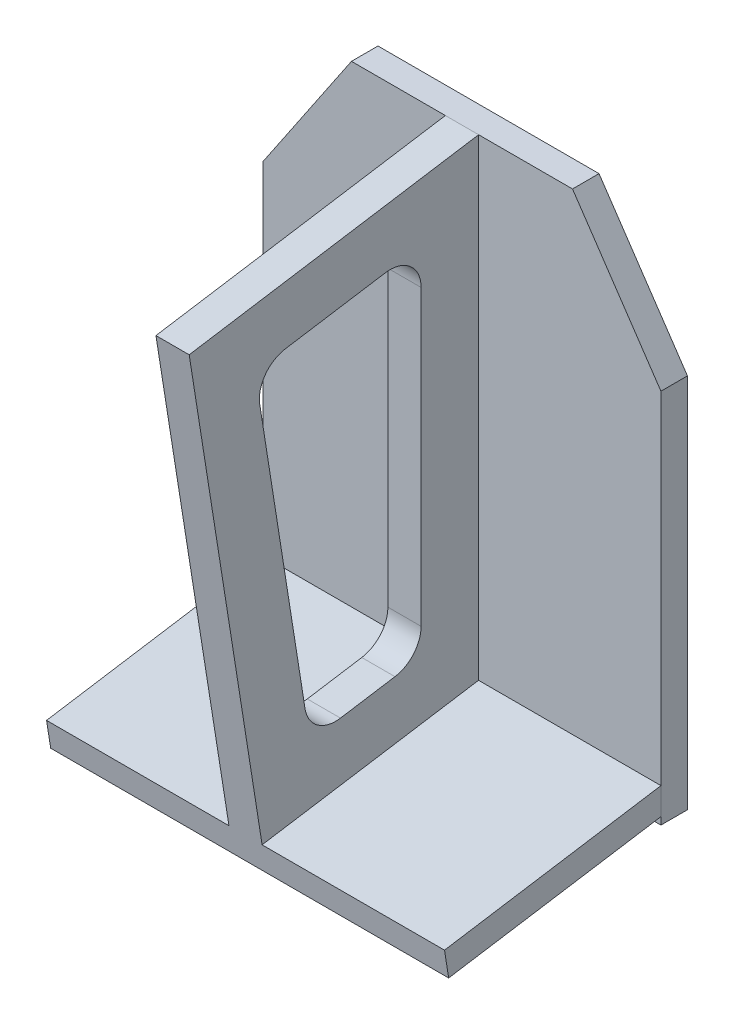
SolidWorks part; units mm, degrees
ref_plane "Front Plane" through (0, 0, 0) normal (0, 0, 1) x (1, 0, 0)
ref_plane "Top Plane" through (0, 0, 0) normal (0, 1, 0) x (1, 0, 0)
ref_plane "Right Plane" through (0, 0, 0) normal (1, 0, 0) x (0, 0, -1)
sketch "Sketch1" plane through (0, 0, 0) normal (0, 0, 1) x (1, 0, 0)
  line L0 (0, 0) -> (0, -68) construction
  line L11 (-45, -68) -> (45, -68)
  line L14 (45, -68) -> (45, 17)
  line L15 (45, 17) -> (25, 46.6204)
  line L16 (25, 46.6204) -> (-25, 46.6204)
  line L17 (-45, -68) -> (-45, 17)
  line L18 (-45, 17) -> (-25, 46.6204)
  point P9 (0, 46.6204)
  dimension "D1" = 90
  dimension "D2" = 85
  dimension "D3" = 50
  dimension "D4" = 68
extrude "Boss-Extrude1" add sketch "Sketch1" along normal blind 6
sketch "Sketch2" plane through (0, -10.1552, 64.1172) normal (0, 0.1564, -0.9877) x (-1, 0, 0)
  line L0 (190, -43.4228) -> (-190, -43.4228) construction
  line L1 (-190, -75.1728) -> (190, -75.1728) construction
  line L2 (190, -43.4228) -> (-190, -43.4228)
  line L3 (-190, -75.1728) -> (190, -75.1728)
  line L4 (-0.1819, -44.9338) -> (-0.0251, -58.5843) construction
  line L5 (-45, -67.1628) -> (-45, 16.7907) construction
  line L6 (45.0187, -64.5843) -> (-45, -64.5843)
  line L7 (45.0187, -64.5843) -> (45.0187, -58.5843)
  line L8 (45.0187, -58.5843) -> (3.7593, -58.5843)
  line L9 (-45, -64.5843) -> (-45, -58.5843)
  line L13 (-25, 46.9851) -> (25, 46.9851) construction
  line L14 (0.0091, -58.5843) -> (0, 46.9851) construction
  line L15 (-3.74, -64.5849) -> (-3.74, -64.5843)
  line L16 (-3.7593, 46.9844) -> (3.7593, 46.9851)
  line L17 (0.0091, -58.5843) -> (-0.0251, -58.5843)
  line L18 (0.0438, -64.5843) -> (0.2006, -78.2347) construction
  line L19 (-3.741, -58.5843) -> (-45, -58.5843)
  line L20 (-3.741, -58.5843) -> (-3.7593, 46.9844)
  line L22 (3.7593, -58.5843) -> (3.7593, 46.9851)
  point P9 (0.0094, -61.5843)
  dimension "D1" = 6
extrude "Boss-Extrude3" add sketch "Sketch2" along normal up to surface (48.6125 mm away) separate body contours L9 L19 L20 L16 L22 L8 L7 L6
sketch "Sketch3" plane through (-3.7593, 0, 0) normal (-1, 0, 0) x (0, 0, 1)
  line L4 (71.4672, 36.2514) -> (6, 46.6204)
  line L5 (6, 46.6204) -> (6, -60.2648)
  line L6 (6, -60.2648) -> (54.9526, -68.0182)
  line L7 (54.9526, -68.0182) -> (71.4672, 36.2514)
  line L8 (71.4672, 36.2514) -> (6, 46.6204)
  line L9 (6, 46.6204) -> (6, -60.2648)
  line L10 (6, -60.2648) -> (54.9526, -68.0182)
  line L11 (54.9526, -68.0182) -> (71.4672, 36.2514)
  line L16 (56.5937, 25.4451) -> (19, 31.3994)
  line L17 (19, 31.3994) -> (19, -49.1618)
  line L18 (19, -49.1618) -> (44.1463, -53.1446)
  line L19 (44.1463, -53.1446) -> (56.5937, 25.4451)
  line L20 (49.6798, 26.5402) -> (27.095, 30.1173)
  line L21 (19, 23.2035) -> (19, -43.1832)
  line L22 (24.905, -50.097) -> (37.2324, -52.0495)
  line L23 (45.2413, -46.2307) -> (55.4986, 18.5313)
  arc A0 (19, -43.1832) -> (24.905, -50.097) centre (26, -43.1832) ccw
  arc A1 (37.2324, -52.0495) -> (45.2413, -46.2307) centre (38.3275, -45.1357) ccw
  arc A2 (49.6798, 26.5402) -> (55.4986, 18.5313) centre (48.5848, 19.6264) cw
  arc A3 (27.095, 30.1173) -> (19, 23.2035) centre (26, 23.2035) ccw
  dimension "D3" = 7
  dimension "D1" = 0
  dimension "D2" = 13
extrude "Cut-Extrude1" cut sketch "Sketch3" along direction (1, -0.0002, 0) on the side against the normal up to surface (7.5163 mm away) contours L22 L23 L20 L21
